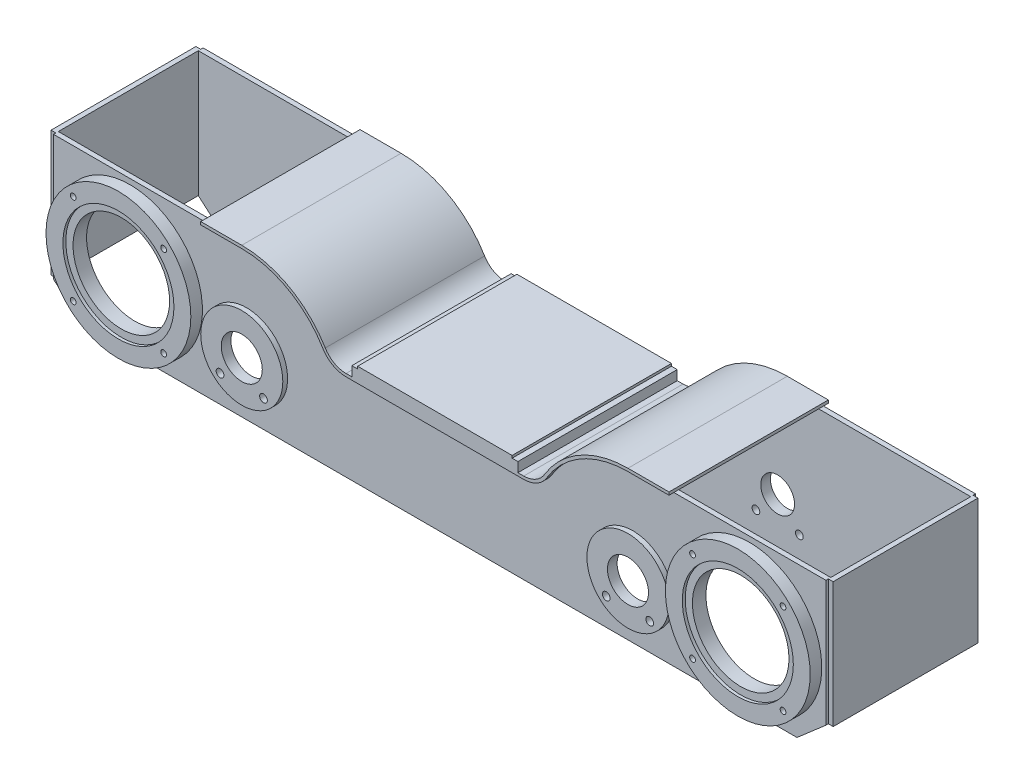
SolidWorks part; units mm, degrees
ref_plane "前视基准面" through (0, 0, 0) normal (0, 0, 1) x (1, 0, 0)
ref_plane "上视基准面" through (0, 0, 0) normal (0, 1, 0) x (1, 0, 0)
ref_plane "右视基准面" through (0, 0, 0) normal (1, 0, 0) x (0, 0, -1)
sketch "草图1" plane through (0, 0, 0) normal (0, 0, 1) x (1, 0, 0)
  line L0 (-1000, 0) -> (49000, 0) construction
  line L1 (0, -1000) -> (0, 49000) construction
  line L2 (-740, 0) -> (740, 0)
  line L3 (740, 0) -> (800, 52)
  line L4 (-740, 0) -> (-800, 52)
  line L5 (800, 52) -> (800, 312)
  line L6 (-800, 52) -> (-800, 312)
  line L7 (-184, 190) -> (184, 190)
  line L8 (-800, 312) -> (-400, 312)
  line L9 (800, 312) -> (400, 312)
  circle A0 centre (-400, 116) radius 35
  circle A1 centre (400, 116) radius 35
  arc A2 (400, 312) -> (232.142, 217.1913) centre (400, 116) ccw
  arc A3 (-400, 312) -> (-232.142, 217.1913) centre (-400, 116) cw
  arc A4 (184, 190) -> (232.142, 217.1913) centre (184, 246.2131) ccw
  arc A5 (-232.142, 217.1913) -> (-184, 190) centre (-184, 246.2131) ccw
  circle A6 centre (-445, 66) radius 8
  circle A7 centre (-355, 66) radius 8
  circle A8 centre (355, 66) radius 8
  circle A9 centre (445, 66) radius 8
  dimension "D12" = 70
  dimension "D13" = 70
  dimension "D22" = 16
  dimension "D1" = 740
  dimension "D2" = 740
  dimension "D3" = 60
  dimension "D4" = 60
  dimension "D5" = 260
  dimension "D6" = 260
  dimension "D7" = 312
  dimension "D8" = 312
  dimension "D9" = 190
  dimension "D10" = 184
  dimension "D11" = 184
  dimension "D14" = 400
  dimension "D15" = 400
  dimension "D16" = 196
  dimension "D21" = 50
  dimension "D23" = 45
  dimension "D24" = 45
  dimension "D25" = 45
  dimension "D26" = 45
extrude "凸台-拉伸1" add sketch "草图1" along normal blind 310
sketch "草图2" plane through (0, 0, 0) normal (0, -1, 0) x (-1, 0, 0)
  line L0 (800, -310) -> (800, 0) construction
  line L2 (800, -300) -> (-800, -300)
  line L4 (800, -300) -> (800, -10)
  line L5 (800, -10) -> (-800, -10)
  line L7 (-800, -300) -> (-800, -10)
  line L8 (-800, -310) -> (-800, 0) construction
  line L9 (740, -310) -> (-740, -310) construction
  line L10 (740, 0) -> (-740, 0) construction
  dimension "D1" = 10
  dimension "D2" = 10
extrude "切除-拉伸1" cut sketch "草图2" against normal through all
sketch "草图3" plane through (0, 0, 310) normal (0, 0, 1) x (1, 0, 0)
  line L0 (0, -1000) -> (0, 49000) construction
  line L1 (-641.4767, 151) -> (-35996.8158, 35506.3391) construction
  line L2 (-641.4767, 151) -> (34713.8624, 35506.3391) construction
  line L3 (641.4767, 151) -> (35996.8158, 35506.3391) construction
  line L4 (641.4767, 151) -> (-34713.8624, 35506.3391) construction
  circle A0 centre (-641.4767, 151) radius 100
  circle A1 centre (-400, 116) radius 35 construction
  circle A2 centre (641.4767, 151) radius 100
  circle A3 centre (-735.1684, 244.6916) radius 6
  circle A4 centre (-547.7851, 244.6916) radius 6
  circle A5 centre (-735.1684, 57.3084) radius 6
  circle A6 centre (-547.7851, 57.3084) radius 6
  circle A7 centre (547.7851, 244.6916) radius 6
  circle A8 centre (735.1684, 244.6916) radius 6
  circle A9 centre (735.1684, 57.3084) radius 6
  circle A10 centre (547.7851, 57.3084) radius 6
  circle A11 centre (-400, 116) radius 42.5
  circle A12 centre (400, 116) radius 42.5
  dimension "D1" = 200
  dimension "D5" = 12
  dimension "D10" = 85
  dimension "D11" = 85
  dimension "D2" = 35
  dimension "D3" = 244
  dimension "D4" = 45
  dimension "D6" = 265
  dimension "D7" = 265
  dimension "D8" = 265
  dimension "D9" = 265
extrude "切除-拉伸2" cut sketch "草图3" against normal blind 10
ref_plane "基准面1" through (0, 0, -10) normal (0, 0, 1) x (1, 0, 0)
sketch "草图5" plane through (0, 0, -10) normal (0, 0, 1) x (1, 0, 0)
  line L0 (485, 312) -> (485, 318)
  line L2 (800, 312) -> (400, 312) construction
  line L3 (-485, 312) -> (-485, 318)
  line L6 (-400, 312) -> (-800, 312) construction
  line L7 (485, 312) -> (400, 312)
  line L8 (-485, 312) -> (-400, 312)
  line L9 (-184, 190) -> (184, 190)
  line L10 (485, 318) -> (400, 318)
  line L11 (0, -1000) -> (0, 49000) construction
  line L12 (-485, 318) -> (-400, 318)
  line L13 (-184, 196) -> (184, 196)
  line L15 (184, 246.2131) -> (400, 116) construction
  line L16 (-400, 116) -> (-184, 246.2131) construction
  arc A0 (-400, 312) -> (-232.142, 217.1913) centre (-400, 116) cw
  arc A1 (-232.142, 217.1913) -> (-184, 190) centre (-184, 246.2131) ccw
  arc A2 (-232.142, 217.1913) -> (-400, 312) centre (-400, 116) ccw construction
  arc A3 (-232.142, 217.1913) -> (-184, 190) centre (-184, 246.2131) ccw construction
  arc A4 (400, 312) -> (232.142, 217.1913) centre (400, 116) ccw
  arc A5 (184, 190) -> (232.142, 217.1913) centre (184, 246.2131) ccw
  arc A6 (184, 190) -> (232.142, 217.1913) centre (184, 246.2131) ccw construction
  arc A8 (400, 312) -> (232.142, 217.1913) centre (400, 116) ccw construction
  arc A9 (-400, 318) -> (-227.0034, 220.289) centre (-400, 116) cw
  arc A10 (-184, 196) -> (-227.0034, 220.289) centre (-184, 246.2131) cw
  arc A11 (400, 318) -> (227.0034, 220.289) centre (400, 116) ccw
  arc A12 (227.0034, 220.289) -> (184, 196) centre (184, 246.2131) cw
  dimension "D1" = 6
  dimension "D2" = 970
  dimension "D3" = 6
extrude "凸台-拉伸2" add sketch "草图5" along normal blind 330
sketch "草图6" plane through (800, 0, 0) normal (1, 0, 0) x (0, 0, -1)
  line L0 (-155, -682) -> (-155, 49318) construction
  line L1 (-305, 312) -> (-5, 312)
  line L2 (-305, 312) -> (-305, 52)
  line L3 (-305, 52) -> (-5, 52)
  line L4 (-5, 312) -> (-5, 52)
  line L6 (-10, 312) -> (0, 312) construction
  line L7 (-10, 52) -> (0, 52) construction
  line L8 (-155, -682) -> (-155, 49318) construction
  line L9 (-320, 318) -> (10, 318) construction
  point P16 (-155, 318)
  dimension "D1" = 150
  dimension "D2" = 150
extrude "凸台-拉伸3" add sketch "草图6" along normal blind 10
sketch "草图7" plane through (-800, 0, 0) normal (-1, 0, 0) x (0, 0, 1)
  line L0 (10, 52) -> (0, 52) construction
  line L1 (5, 52) -> (305, 52)
  line L2 (5, 52) -> (5, 312)
  line L3 (5, 312) -> (305, 312)
  line L4 (305, 52) -> (305, 312)
  line L5 (310, 312) -> (300, 312) construction
  line L6 (155, -682) -> (155, 49318) construction
  line L8 (155, -682) -> (155, 49318) construction
  line L9 (320, 318) -> (-10, 318) construction
  point P15 (155, 318)
  dimension "D1" = 150
  dimension "D2" = 150
extrude "凸台-拉伸4" add sketch "草图7" along normal blind 10
sketch "草图9" plane through (0, 190, 0) normal (0, -1, 0) x (1, 0, 0)
  line L1 (-110, 300) -> (-100, 300)
  line L2 (-110, 300) -> (-110, 10)
  line L3 (-110, 10) -> (-100, 10)
  line L4 (-100, 300) -> (-100, 10)
  line L5 (-740, 10) -> (740, 10) construction
  line L6 (740, 300) -> (-740, 300) construction
  line L7 (100, 300) -> (110, 300)
  line L8 (100, 300) -> (100, 10)
  line L9 (100, 10) -> (110, 10)
  line L10 (110, 300) -> (110, 10)
  line L12 (150, 300) -> (160, 300)
  line L13 (150, 300) -> (150, 10)
  line L14 (150, 10) -> (160, 10)
  line L15 (160, 300) -> (160, 10)
  line L16 (0, -1000) -> (0, 49000) construction
  line L17 (-160, 300) -> (-150, 300)
  line L18 (-160, 300) -> (-160, 10)
  line L19 (-160, 10) -> (-150, 10)
  line L20 (-150, 300) -> (-150, 10)
  dimension "D1" = 10
  dimension "D2" = 220
  dimension "D3" = 320
extrude "凸台-拉伸5" add sketch "草图9" along normal blind 184
sketch "草图10" plane through (0, 6, 0) normal (0, -1, 0) x (1, 0, 0)
  line L0 (0, -1000) -> (0, 49000) construction
  line L1 (100, 300) -> (-100, 300) construction
  line L2 (-210, 300) -> (210, 300)
  line L3 (-210, 300) -> (-210, 10)
  line L4 (-210, 10) -> (210, 10)
  line L5 (210, 300) -> (210, 10)
  line L6 (-740, 10) -> (740, 10) construction
  dimension "D1" = 210
  dimension "D2" = 210
extrude "凸台-拉伸6" add sketch "草图10" along normal blind 6
sketch "草图11" plane through (0, 0, 310) normal (0, 0, 1) x (1, 0, 0)
  circle A0 centre (-400, 116) radius 85
  circle A1 centre (-400, 116) radius 42.5
  circle A2 centre (-445, 66) radius 8
  circle A3 centre (-355, 66) radius 8
  circle A4 centre (-445, 66) radius 8 construction
  circle A5 centre (-355, 66) radius 8 construction
  circle A7 centre (-400, 116) radius 42.5 construction
  dimension "D1" = 170
extrude "凸台-拉伸7" add sketch "草图11" along normal blind 10
sketch "草图12" plane through (0, 0, 0) normal (0, 0, -1) x (-1, 0, 0)
  circle A0 centre (400, 116) radius 85
  circle A1 centre (400, 116) radius 35
  circle A2 centre (400, 116) radius 35 construction
  circle A3 centre (355, 66) radius 8
  circle A4 centre (445, 66) radius 8
  circle A5 centre (355, 66) radius 8 construction
  circle A6 centre (445, 66) radius 8 construction
  dimension "D1" = 170
extrude "凸台-拉伸8" add sketch "草图12" along normal blind 10
pattern_linear "阵列(线性)2" count 2 spacing 800 along (1, 0, 0) of "凸台-拉伸7", "凸台-拉伸8"
sketch "草图13" plane through (0, 0, 310) normal (0, 0, 1) x (1, 0, 0)
  circle A0 centre (-641.4767, 151) radius 150
  circle A1 centre (-641.4767, 151) radius 100
  circle A2 centre (-641.4767, 151) radius 100 construction
  circle A3 centre (-735.1684, 244.6916) radius 6
  circle A4 centre (-547.7851, 244.6916) radius 6
  circle A5 centre (-547.7851, 57.3084) radius 6
  circle A6 centre (-735.1684, 57.3084) radius 6
  circle A7 centre (-735.1684, 244.6916) radius 6 construction
  circle A8 centre (-547.7851, 244.6916) radius 6 construction
  circle A9 centre (-547.7851, 57.3084) radius 6 construction
  circle A10 centre (-735.1684, 57.3084) radius 6 construction
  circle A11 centre (735.1684, 244.6916) radius 6
  circle A12 centre (547.7851, 57.3084) radius 6
  circle A13 centre (735.1684, 57.3084) radius 6
  circle A14 centre (547.7851, 244.6916) radius 6
  circle A15 centre (641.4767, 151) radius 100
  circle A16 centre (641.4767, 151) radius 100 construction
  circle A17 centre (547.7851, 244.6916) radius 6 construction
  circle A18 centre (735.1684, 244.6916) radius 6 construction
  circle A19 centre (735.1684, 57.3084) radius 6 construction
  circle A20 centre (547.7851, 57.3084) radius 6 construction
  circle A21 centre (641.4767, 151) radius 150
  dimension "D1" = 300
  dimension "D2" = 300
extrude "凸台-拉伸9" add sketch "草图13" along normal blind 24
sketch "草图14" plane through (0, 0, 334) normal (0, 0, 1) x (1, 0, 0)
  circle A0 centre (-641.4767, 151) radius 115
  circle A1 centre (-641.4767, 151) radius 100 construction
  circle A2 centre (641.4767, 151) radius 115
  circle A3 centre (641.4767, 151) radius 150 construction
  dimension "D1" = 230
  dimension "D2" = 230
extrude "切除-拉伸3" cut sketch "草图14" against normal blind 6
sketch "草图17" plane through (0, 196, 0) normal (0, 1, 0) x (1, 0, 0)
  line L0 (0, -1320) -> (0, 48680) construction
  line L1 (184, -320) -> (-184, -320) construction
  line L2 (184, 10) -> (-184, 10) construction
  line L3 (-172, 10) -> (172, 10)
  line L4 (-172, 10) -> (-172, -320)
  line L5 (-172, -320) -> (172, -320)
  line L6 (172, 10) -> (172, -320)
  point P5 (0, -320)
  dimension "D1" = 172
  dimension "D2" = 172
extrude "凸台-拉伸11" add sketch "草图17" along normal blind 20
sketch "草图16" plane through (0, 216, 0) normal (0, 1, 0) x (1, 0, 0)
  line L0 (184, 10) -> (172, 10) construction
  line L1 (-160, 10) -> (160, 10)
  line L2 (-160, 10) -> (-160, -320)
  line L3 (-160, -320) -> (160, -320)
  line L4 (160, 10) -> (160, -320)
  line L5 (184, -320) -> (172, -320) construction
  dimension "D1" = 160
  dimension "D2" = 160
extrude "凸台-拉伸10" add sketch "草图16" along normal blind 5
